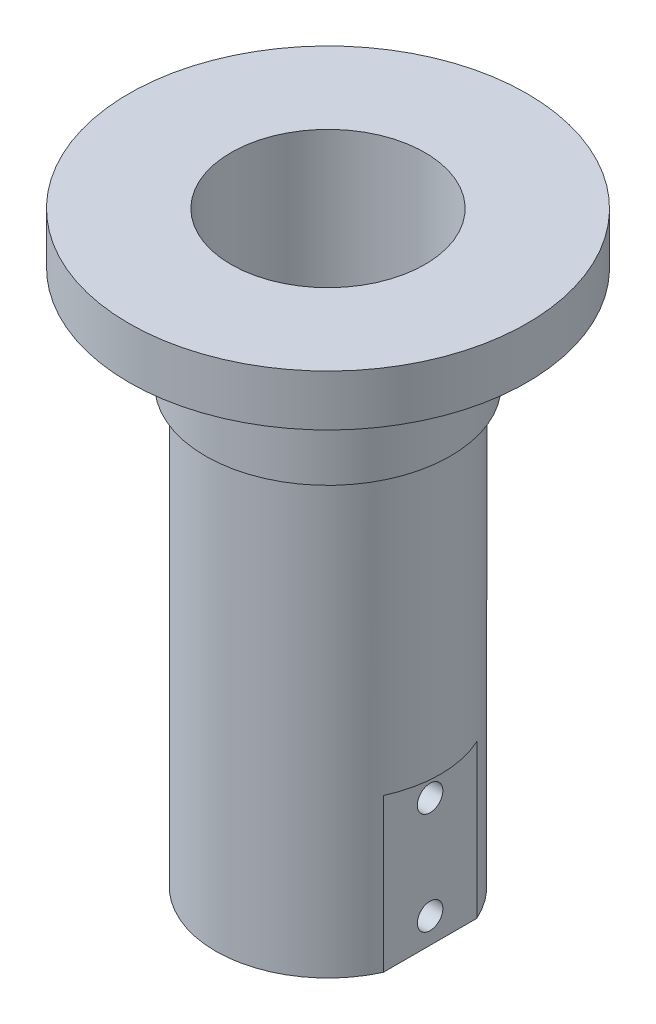
SolidWorks part; units mm, degrees
material "AISI 304"
ref_plane "前视基准面" through (0, 0, 0) normal (0, 0, 1) x (1, 0, 0)
ref_plane "上视基准面" through (0, 0, 0) normal (0, 1, 0) x (1, 0, 0)
ref_plane "右视基准面" through (0, 0, 0) normal (1, 0, 0) x (0, 0, -1)
sketch "Sketch1" plane through (0, 0, 0) normal (0, 0, 1) x (1, 0, 0)
  line L0 (0, 66.9595) -> (0, -48.0405) construction
  line L1 (19, 66.9595) -> (39, 66.9595)
  line L2 (39, 66.9595) -> (39, 56.9595)
  line L3 (39, 56.9595) -> (24, 56.9595)
  line L4 (22, 36.9595) -> (22, -48.0405)
  line L5 (22, -48.0405) -> (12.5, -48.0405)
  line L6 (8.5, -34.0405) -> (8.5, -14.0405)
  line L7 (8.5, -14.0405) -> (19, -14.0405)
  line L8 (19, -14.0405) -> (19, 66.9595)
  line L9 (10.5, -41.0405) -> (10.5, -34.0405)
  line L10 (10.5, -34.0405) -> (8.5, -34.0405)
  line L11 (24, 56.9595) -> (24, 36.9595)
  line L12 (24, 36.9595) -> (22, 36.9595)
  line L13 (12.5, -48.0405) -> (12.5, -41.0405)
  line L14 (12.5, -41.0405) -> (10.5, -41.0405)
  dimension "D1" = 19
  dimension "D2" = 20
  dimension "D3" = 12.5
  dimension "D4" = 2
  dimension "D5" = 7
  dimension "D6" = 20
  dimension "D7" = 2
  dimension "D8" = 10
  dimension "D9" = 10.5
  dimension "D10" = 44
  dimension "D11" = 20
  dimension "D12" = 17
  dimension "D13" = 7
revolve "Revolve1" add sketch "Sketch1" angle 360 about L0
sketch "Sketch2" plane through (0, -48.0405, 0) normal (0, -1, 0) x (1, 0, 0)
  line L1 (11, -11) -> (-11, -11) construction
  line L2 (11, -11) -> (11, 11) construction
  line L3 (11, 11) -> (-11, 11) construction
  line L4 (-11, -11) -> (-11, 11) construction
  line L5 (11, -11) -> (-11, 11) construction
  line L6 (11, 11) -> (-11, -11) construction
  point P0 (0, 0)
  dimension "D1" = 22
hole_wizard "M3 Tapped Hole1" positions "3DSketch1" profile "Sketch3" tap size "M3" standard "GB"
sketch3d "3DSketch1"
  point P0 (-11, -48.0405, 11)
  point P3 (11, -48.0405, 11)
  point P6 (-11, -48.0405, -11)
  point P9 (11, -48.0405, -11)
sketch "Sketch3" plane through (-11, -48.0405, 11) normal (1, 0, 0) x (0, 0, -1)
  line L0 (0, 0) -> (0, 8.2511)
  line L1 (0, 8.2511) -> (1.25, 7.5)
  line L2 (1.25, 7.5) -> (1.25, 0)
  line L5 (1.25, 0) -> (0, 0)
  line L10 (0, 8.2511) -> (-1.25, 7.5) construction
  line L11 (0, -6.35) -> (0, 107.95) construction
  dimension "螺纹孔钻头直径" = 2.5
  dimension "螺纹孔钻头深度" = 7.5
  dimension "导头角度" = 118
cosmetic thread "Cosmetic Thread1" parameters "D1"=6, "D2"=3
cosmetic thread "Cosmetic Thread2" parameters "D1"=6, "D2"=3
cosmetic thread "Cosmetic Thread3" parameters "D1"=6, "D2"=3
cosmetic thread "Cosmetic Thread4" parameters "D1"=6, "D2"=3
sketch "Sketch4" plane through (0, -48.0405, 0) normal (0, -1, 0) x (1, 0, 0)
  line L1 (20, -29.4944) -> (-20, -29.4944)
  line L2 (20, -29.4944) -> (20, 29.4944)
  line L3 (20, 29.4944) -> (-20, 29.4944)
  line L4 (-20, -29.4944) -> (-20, 29.4944)
  line L5 (20, -29.4944) -> (-20, 29.4944) construction
  line L6 (20, 29.4944) -> (-20, -29.4944) construction
  circle A0 centre (0, 0) radius 12.5 construction
  point P0 (0, 0)
  dimension "D1" = 20
extrude "Extrude1" cut sketch "Sketch4" against normal blind 30 flip side to cut
sketch "Sketch5" plane through (-20, 0, 0) normal (-1, 0, 0) x (0, 0, 1)
  line L0 (0, -48.0405) -> (0, -18.0405) construction
  line L1 (-9.1652, -48.0405) -> (9.1652, -48.0405) construction
  line L2 (9.1652, -18.0405) -> (-9.1652, -18.0405) construction
  line L3 (-9.1652, -33.0405) -> (9.1652, -33.0405) construction
  line L4 (-9.1652, -18.0405) -> (-9.1652, -48.0405) construction
  line L5 (9.1652, -48.0405) -> (9.1652, -18.0405) construction
  point P12 (0, -23.0405)
  point P13 (0, -43.0405)
  dimension "D1" = 10
hole_wizard "M6 Tapped Hole1" positions "3DSketch2" profile "Sketch6" tap size "M6" standard "GB" end condition through all
sketch3d "3DSketch2"
  point P0 (-20, -23.0405, 0)
  point P3 (-20, -43.0405, 0)
cosmetic thread "Cosmetic Thread5" parameters "D2"=6
cosmetic thread "Cosmetic Thread6" parameters "D2"=6
sketch "Sketch6" plane through (-20, -23.0405, 0) normal (0, 1, 0) x (0, 0, 1)
  line L0 (0, 0) -> (0, 59)
  line L1 (0, 59) -> (2.5, 59)
  line L2 (2.5, 59) -> (2.5, 0)
  line L5 (2.5, 0) -> (0, 0)
  line L11 (0, -6.35) -> (0, 107.95) construction
  dimension "通孔螺纹孔钻头直径" = 5
  dimension "通孔螺纹孔钻头深度" = 59
